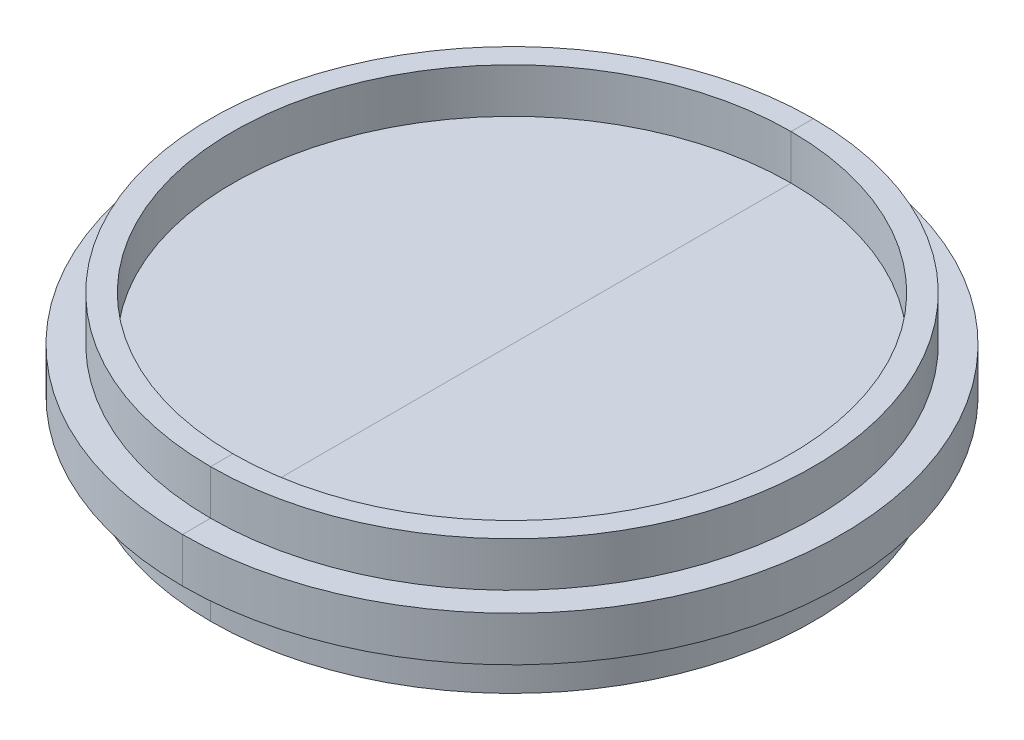
SolidWorks part; units mm, degrees
ref_plane "Front Plane" through (0, 0, 0) normal (0, 0, 1) x (1, 0, 0)
ref_plane "Top Plane" through (0, 0, 0) normal (0, 1, 0) x (1, 0, 0)
ref_plane "Right Plane" through (0, 0, 0) normal (1, 0, 0) x (0, 0, -1)
sketch "Sketch1" plane through (0, 0, 0) normal (0, 1, 0) x (1, 0, 0)
  circle A0 centre (0, 0) radius 93.726
  dimension "D1" = 187.452
extrude "Boss-Extrude1" add sketch "Sketch1" along normal mid plane 12.7
sketch "Sketch5" plane through (0, 6.35, 0) normal (0, 1, 0) x (1, 0, 0)
  circle A0 centre (0, 0) radius 85.725
  circle A1 centre (0, 0) radius 79.375
  dimension "D1" = 171.45
  dimension "D2" = 158.75
extrude "Boss-Extrude2" add sketch "Sketch5" along normal blind 12.7
ref_plane "Plane1" through (0, 0, -85.725) normal (0, 0, -1) x (-1, 0, 0)
sketch "Sketch6" plane through (0, 0, -85.725) normal (0, 0, -1) x (-1, 0, 0)
  line L0 (0, 55) -> (0, -55) construction
  line L1 (93.726, 6.35) -> (-93.726, 6.35) construction
  circle A0 centre (0, 12.7) radius 1.4351
  dimension "D1" = 2.8702
  dimension "D2" = 6.35
extrude "Cut-Extrude1" [suppressed] cut sketch "Sketch6" against normal blind 12.7
pattern_circular "CirPattern1" [suppressed] count 12 over 360
mirror "Mirror1" about plane through (0, 0, 0) normal (0, 1, 0) of "CirPattern1", "Cut-Extrude1", "Boss-Extrude2"
sketch "Sketch7" plane through (0, 19.05, 0) normal (0, 1, 0) x (1, 0, 0)
  line L0 (-25.7878, 75.0692) -> (-28.1663, 80.9657)
  line L1 (28.1663, 80.9657) -> (25.7878, 75.0692)
  arc A0 (28.1663, 80.9657) -> (-28.1663, 80.9657) centre (0, 0) ccw
  circle A1 centre (0, 0) radius 85.725 construction
  arc A2 (25.7878, 75.0692) -> (-25.7878, 75.0692) centre (0, 0) ccw
  circle A3 centre (0, 0) radius 79.375 construction
extrude "Boss-Extrude3" add sketch "Sketch7" against normal up to surface (25.4 mm away)
mirror "Mirror3" about plane through (0, 0, 0) normal (0, 1, 0) of "Boss-Extrude3"
mirror "Mirror4" about plane through (0, 0, 0) normal (0, 0, 1) of "Boss-Extrude3"
mirror "Mirror5" about plane through (0, 0, 0) normal (0, 1, 0) of "Mirror4"
sketch "Sketch4" plane through (0, 0, 0) normal (0, 0, 1) x (1, 0, 0)
  line L0 (0, 23.2786) -> (0, -14.9525) construction
sketch "Sketch3" [suppressed] plane through (0, 0, 0) normal (0, 0, 1) x (1, 0, 0)
  line L0 (-31.75, -6.35) -> (-56.6752, 6.35)
  line L1 (93.726, 6.35) -> (-93.726, 6.35) construction
  line L2 (-56.6752, 6.35) -> (-31.75, 6.35)
  line L3 (-31.75, 6.35) -> (-31.75, -6.35)
  line L4 (-31.75, -6.35) -> (31.75, -6.35) construction
  line L5 (31.75, 6.35) -> (-31.75, 6.35) construction
  dimension "D1" = 27
revolve "Cut-Revolve1" [suppressed] cut sketch "Sketch3" angle 360 about L0
split "Split1" trim tools "Right Plane" bodies to split 114 resulting bodies 104 105
